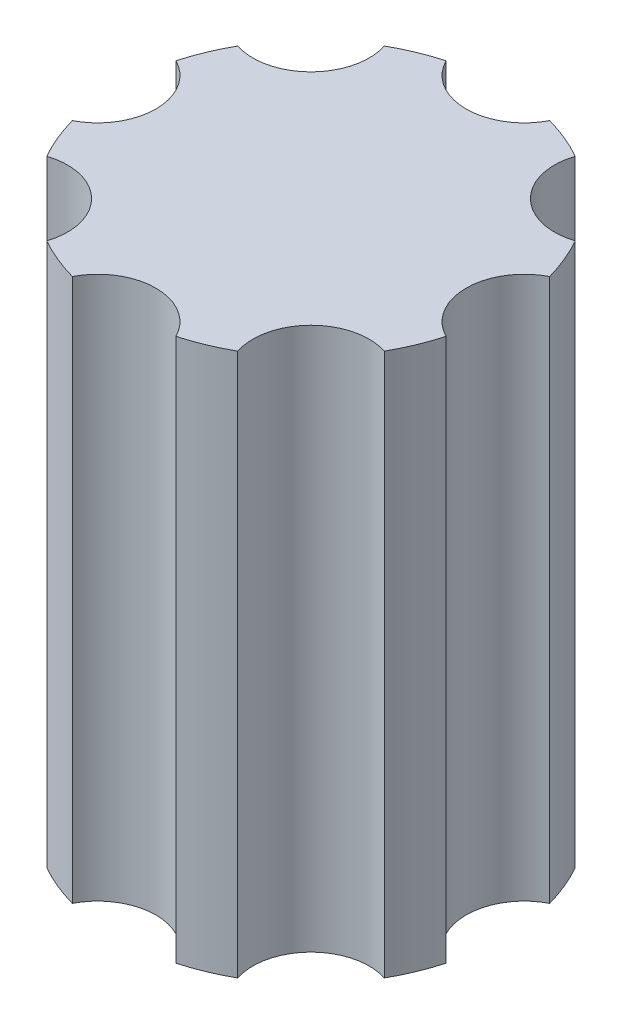
SolidWorks part; units mm, degrees
ref_plane "Plan de face" through (0, 0, 0) normal (0, 0, 1) x (1, 0, 0)
ref_plane "Plan de dessus" through (0, 0, 0) normal (0, 1, 0) x (1, 0, 0)
ref_plane "Plan de droite" through (0, 0, 0) normal (1, 0, 0) x (0, 0, -1)
sketch "Esquisse1" plane through (0, 0, 0) normal (0, 1, 0) x (1, 0, 0)
  line L0 (-2.2361, -2) -> (2.2361, -2)
  circle A0 centre (0, 0) radius 5
  circle A1 centre (0, 0) radius 3
  dimension "D1" = 10
  dimension "D2" = 2
  dimension "D3" = 6
extrude "Boss.-Extru.1" add sketch "Esquisse1" along normal blind 12 contours A0 A1 | L0 A1
sketch "Esquisse2" plane through (0, 12, 0) normal (0, 1, 0) x (1, 0, 0)
  circle A0 centre (0, 0) radius 5
  circle A1 centre (0, 0) radius 5 construction
extrude "Boss.-Extru.2" add sketch "Esquisse2" along normal blind 2
sketch "Esquisse3" plane through (0, 14, 0) normal (0, 1, 0) x (1, 0, 0)
  circle A0 centre (0, 5.5) radius 1.5
  point P2 (0, 0)
  dimension "D1" = 5.5
  dimension "D2" = 3
extrude "Enlèv. mat.-Extru.1" cut sketch "Esquisse3" against normal up to vertex (14 mm away) up to point (0, 0, 0)
pattern_circular "Répétition circulaire1" count 8 over 360 about axis through (0, 0, 0) along (0, 1, 0) of "Enlèv. mat.-Extru.1"
